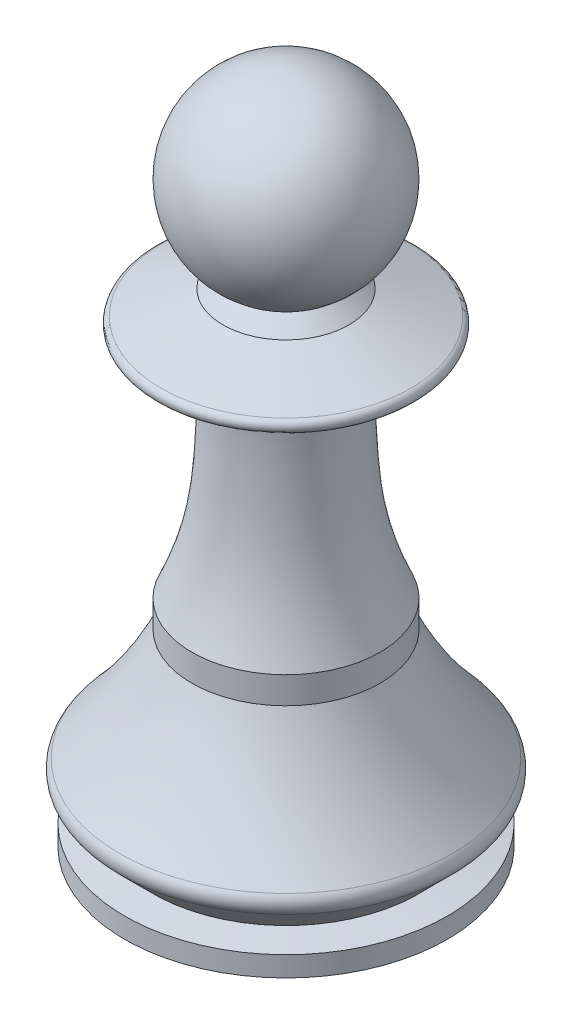
SolidWorks part; units mm, degrees
material "Maple"
ref_plane "Front Plane" through (0, 0, 0) normal (0, 0, 1) x (1, 0, 0)
ref_plane "Top Plane" through (0, 0, 0) normal (0, 1, 0) x (1, 0, 0)
ref_plane "Right Plane" through (0, 0, 0) normal (1, 0, 0) x (0, 0, -1)
sketch "Sketch6" plane through (0, 0, 0) normal (0, 0, 1) x (1, 0, 0)
  line L0 (0, 0) -> (0, 50)
  line L1 (0, 0) -> (12, 0)
  line L2 (12, 0) -> (12, 3.0957) construction
  line L3 (0, 36) -> (9, 36) construction
  line L4 (9, 36) -> (9, 32.5) construction
  line L5 (9, 32.5) -> (0, 32.5) construction
  line L6 (12, 0) -> (12, 1.5)
  line L7 (12, 1.5) -> (9.8747, 1.8747)
  line L9 (0, 43) -> (3.5, 36.9378) construction
  line L11 (11, 33.5) -> (5, 32.5)
  line L13 (7, 14) -> (7, 16)
  line L14 (9.8747, 1.8747) -> (13, 5)
  line L16 (12, 3.0957) -> (12, 0) construction
  line L18 (3.5, 36.9378) -> (4.6918, 35.9378)
  line L19 (4.6918, 35.9378) -> (11, 33.5)
  arc A0 (0, 50) -> (0, 36) centre (0, 43) cw construction
  arc A1 (0, 50) -> (3.5, 36.9378) centre (0, 43) cw
  spline S0 degree 2 poles (12, 3.0957) (2.5166, 14.8814) (5, 32.5) knots 0 0 0 1 1 1 construction
  spline S1 degree 2 poles (7, 14) (9.1788, 9.005) (13, 5) knots 0 0 0 1 1 1
  spline S2 degree 3 poles (5, 32.5) (4.6326, 30.3602) (4.7601, 24.4105) (5.3037, 19.8693) (7, 16) knots 0 0 0 0 0.393038 1 1 1 1
  dimension "D1" = 12
  dimension "D2" = 50
  dimension "D3" = 14
  dimension "D5" = 3.5
  dimension "D7" = 100
  dimension "D8" = 30
  dimension "D9" = 1.5
  dimension "D11" = 5
  dimension "D12" = 1
  dimension "D16" = 2
  dimension "D17" = 14
  dimension "D4" = 55
  dimension "D10" = 1
  dimension "D18" = 5
  dimension "D19" = 3.0957
  dimension "D20" = 7
  dimension "D14" = 1
  dimension "D21" = 40
  dimension "D13" = 11
revolve "Revolve1" add sketch "Sketch6" angle 360 about L0
fillet "Fillet1" radius 1 1 edges at (0, 5, -13)
fillet "Fillet2" radius 0.5 1 edges at (0, 33.5, -11)
equation "\"baseRadius\"= 12mm"
equation "\"D1@Sketch6\" = \"baseRadius\""
equation "\"height\"= 50.000mm"
equation "\"D2@Sketch6\"=\"height\""
equation "\"topDiameter\"= 14mm"
equation "\"D3@Sketch6\"=\"topDiameter\""
equation "\"D11@Sketch6\"=(\"baseRadius\"/2)-1"
equation "\"D20@Sketch6\"=(\"baseRadius\"/2)+1"
equation "\"D17@Sketch6\"=\"baseRadius\"+2"
equation "\"upperRadius\"= 11mm"
equation "\"D13@Sketch6\"=\"upperRadius\""
